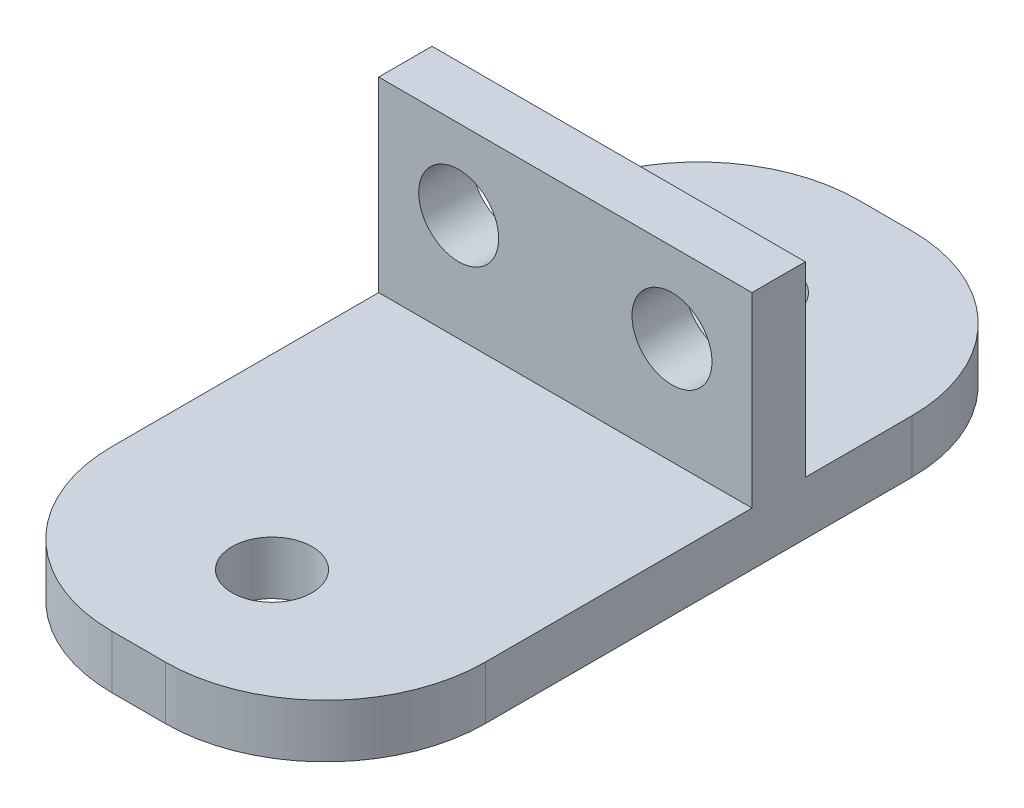
SolidWorks part; units mm, degrees
ref_plane "Спереди" through (0, 0, 0) normal (0, 0, 1) x (1, 0, 0)
ref_plane "Сверху" through (0, 0, 0) normal (0, 1, 0) x (1, 0, 0)
ref_plane "Справа" through (0, 0, 0) normal (1, 0, 0) x (0, 0, -1)
sketch "Эскиз1" plane through (0, 0, 0) normal (0, -1, 0) x (1, 0, 0)
  line L1 (0, 0) -> (14, 0)
  line L2 (0, 0) -> (0, -28)
  line L3 (0, -28) -> (14, -28)
  line L4 (14, 0) -> (14, -28)
  dimension "D1" = 14
  dimension "D2" = 28
extrude "Бобышка-Вытянуть1" add sketch "Эскиз1" along normal blind 2
sketch "Эскиз2" plane through (0, -2, 0) normal (0, -1, 0) x (1, 0, 0)
  line L0 (14, 0) -> (0, 0) construction
  circle A0 centre (7, -5) radius 1.5
  circle A1 centre (7, -23) radius 1.5
  point P7 (7, 0)
  dimension "D1" = 3
  dimension "D2" = 18
  dimension "D3" = 5
extrude "Вырез-Вытянуть1" cut sketch "Эскиз2" against normal blind 2
sketch "Эскиз3" plane through (0, 0, 0) normal (0, 1, 0) x (1, 0, 0)
  line L0 (0, 0) -> (0, 28) construction
  line L1 (0, 16) -> (14, 16)
  line L2 (0, 16) -> (0, 18)
  line L3 (0, 18) -> (14, 18)
  line L4 (14, 16) -> (14, 18)
  line L5 (14, 28) -> (14, 0) construction
  point P8 (14, 14)
  dimension "D1" = 2
  dimension "D2" = 2
extrude "Бобышка-Вытянуть2" add sketch "Эскиз3" along normal blind 7
fillet "Скругление1" radius 6 4 edges at (0, -1, 0) (14, -1, 0) (14, -1, -28) (0, -1, -28)
sketch "Эскиз4" plane through (0, 0, -18) normal (0, 0, -1) x (-1, 0, 0)
  line L0 (-11, 4) -> (-3, 4) construction
  line L1 (-14, 7) -> (0, 7) construction
  line L2 (-14, 7) -> (-14, 0) construction
  circle A0 centre (-11, 4) radius 1.5
  circle A1 centre (-3, 4) radius 1.5
  point P4 (-7, 4)
  point P7 (-7, 7)
  dimension "D3" = 3
  dimension "D1" = 3
  dimension "D2" = 3
extrude "Вырез-Вытянуть2" cut sketch "Эскиз4" against normal blind 15
